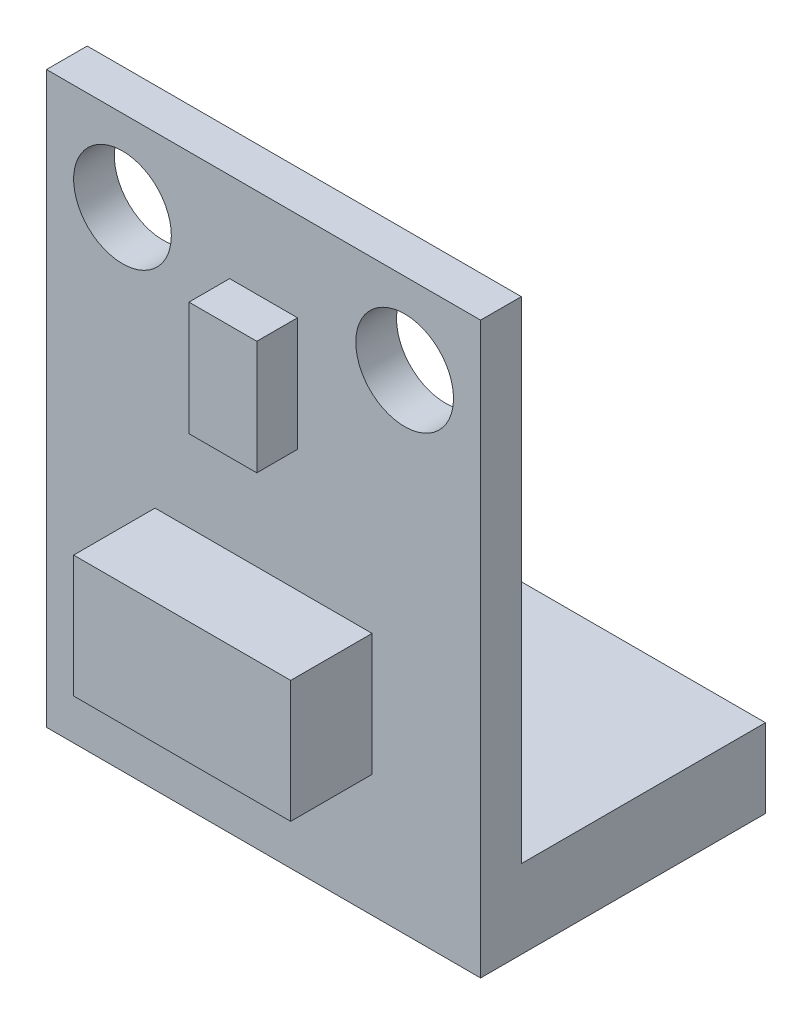
SolidWorks part; units mm, degrees
ref_plane "Front Plane" through (0, 0, 0) normal (0, 0, 1) x (1, 0, 0)
ref_plane "Top Plane" through (0, 0, 0) normal (0, 1, 0) x (1, 0, 0)
ref_plane "Right Plane" through (0, 0, 0) normal (1, 0, 0) x (0, 0, -1)
sketch "Sketch1" plane through (0, 0, 0) normal (0, 0, 1) x (1, 0, 0)
  line L0 (-5.2, 9.3) -> (-7, 9.3) construction
  line L1 (-8, 10.5) -> (8, 10.5)
  line L2 (-8, 10.5) -> (-8, -10.5)
  line L3 (-8, -10.5) -> (8, -10.5)
  line L4 (8, 10.5) -> (8, -10.5)
  line L5 (-8, 10.5) -> (8, -10.5) construction
  line L6 (-8, -10.5) -> (8, 10.5) construction
  line L7 (-7, 9.3) -> (-7, 7.5) construction
  line L8 (0, 0) -> (0, 10.5) construction
  circle A0 centre (-5.2, 7.5) radius 1.8
  circle A1 centre (5.2, 7.5) radius 1.8
  point P0 (0, 0)
  dimension "D3" = 3.6
  dimension "D1" = 16
  dimension "D2" = 21
  dimension "D4" = 1
  dimension "D5" = 1.2
extrude "Boss-Extrude1" add sketch "Sketch1" along normal blind 1.5
sketch "Sketch2" plane through (0, 0, 1.5) normal (0, 0, 1) x (1, 0, 0)
  line L0 (0, 0) -> (0, 5.1) construction
  line L1 (8, 10.5) -> (-8, 10.5) construction
  line L2 (-1.25, 7.2) -> (1.25, 7.2)
  line L3 (-1.25, 7.2) -> (-1.25, 3)
  line L4 (-1.25, 3) -> (1.25, 3)
  line L5 (1.25, 7.2) -> (1.25, 3)
  line L6 (-1.25, 7.2) -> (1.25, 3) construction
  line L7 (-1.25, 3) -> (1.25, 7.2) construction
  dimension "D1" = 4.2
  dimension "D2" = 2.5
  dimension "D3" = 7.5
extrude "Boss-Extrude2" add sketch "Sketch2" along normal blind 1.5
sketch "Sketch3" plane through (0, 0, 1.5) normal (0, 0, 1) x (1, 0, 0)
  line L0 (0, 0) -> (0, -3.75) construction
  line L1 (-4, -1.5) -> (4, -1.5)
  line L2 (-4, -1.5) -> (-4, -6)
  line L3 (-4, -6) -> (4, -6)
  line L4 (4, -1.5) -> (4, -6)
  line L5 (-4, -1.5) -> (4, -6) construction
  line L6 (-4, -6) -> (4, -1.5) construction
  line L7 (-8, -10.5) -> (8, -10.5) construction
  point P0 (0, -3.75)
  dimension "D1" = 8
  dimension "D2" = 4.5
  dimension "D3" = 9
extrude "Boss-Extrude3" add sketch "Sketch3" along normal blind 3
sketch "Sketch4" plane through (0, 0, 0) normal (0, 0, -1) x (-1, 0, 0)
  line L0 (8, 10.5) -> (8, -10.5) construction
  line L1 (-8, -10.5) -> (8, -10.5)
  line L2 (-8, -10.5) -> (-8, -7.6)
  line L3 (-8, -7.6) -> (8, -7.6)
  line L4 (8, -10.5) -> (8, -7.6)
  dimension "D1" = 2.9
extrude "Boss-Extrude4" add sketch "Sketch4" along normal blind 9
